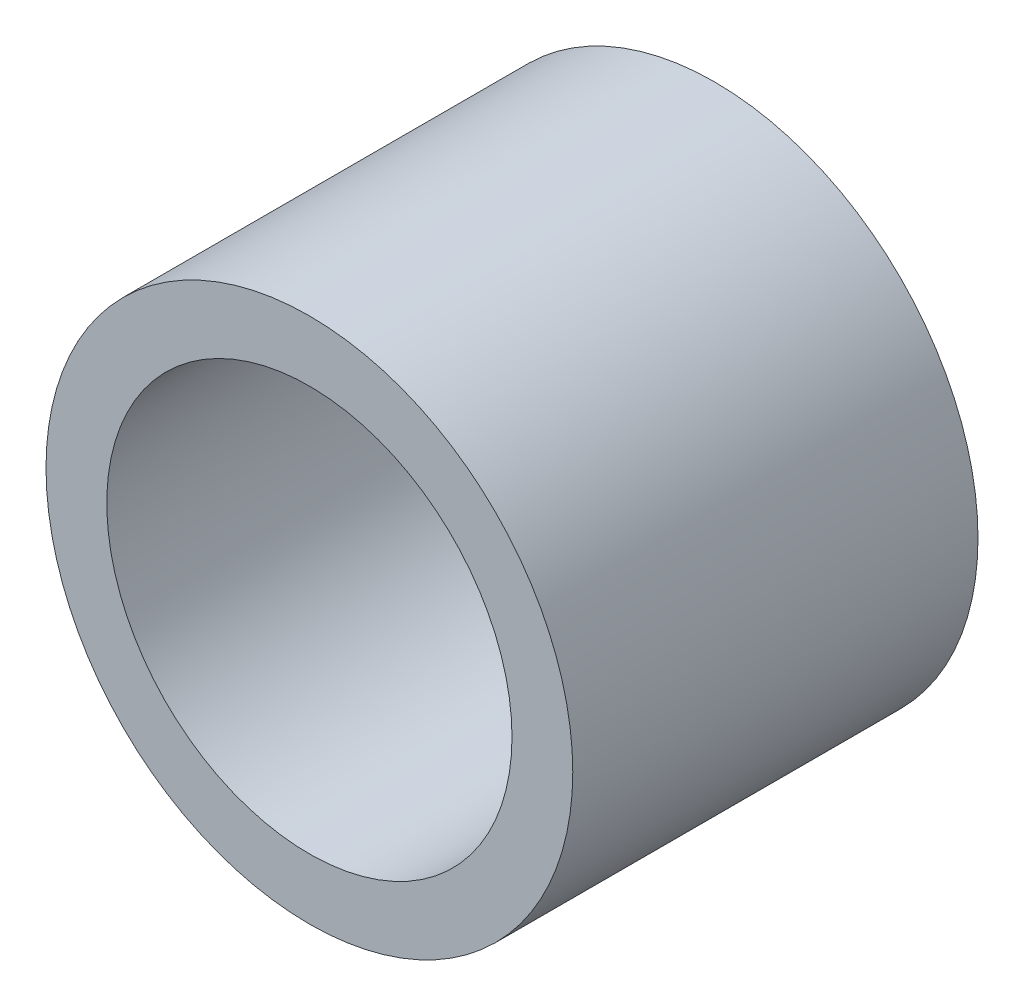
SolidWorks part; units mm, degrees
ref_plane "Front Plane" through (0, 0, 0) normal (0, 0, 1) x (1, 0, 0)
ref_plane "Top Plane" through (0, 0, 0) normal (0, 1, 0) x (1, 0, 0)
ref_plane "Right Plane" through (0, 0, 0) normal (1, 0, 0) x (0, 0, -1)
sketch "Sketch1" plane through (0, 0, 0) normal (0, 0, 1) x (1, 0, 0)
  circle A0 centre (0, 0) radius 13
  circle A1 centre (0, 0) radius 10
  dimension "D1" = 26
  dimension "ID" = 20
extrude "Extrude1" add sketch "Sketch1" along normal mid plane 20
sketch "Sketch2" plane through (0, 0, 0) normal (1, 0, 0) x (0, 0, -1)
  line L0 (-10, -10) -> (10, -10) construction
  line L3 (10, 10) -> (-10, 10) construction
  line L5 (-10, -10) -> (10, -10)
  line L6 (10, 10) -> (-10, 10)
sketch "Sketch4" plane through (0, 0, 10) normal (0, 0, 1) x (1, 0, 0)
  line L0 (0, 0) -> (-7.0711, 7.0711)
  line L1 (0, -8.8) -> (0, 8.8) construction
  circle A0 centre (0, 0) radius 10 construction
  dimension "D1" = 45
